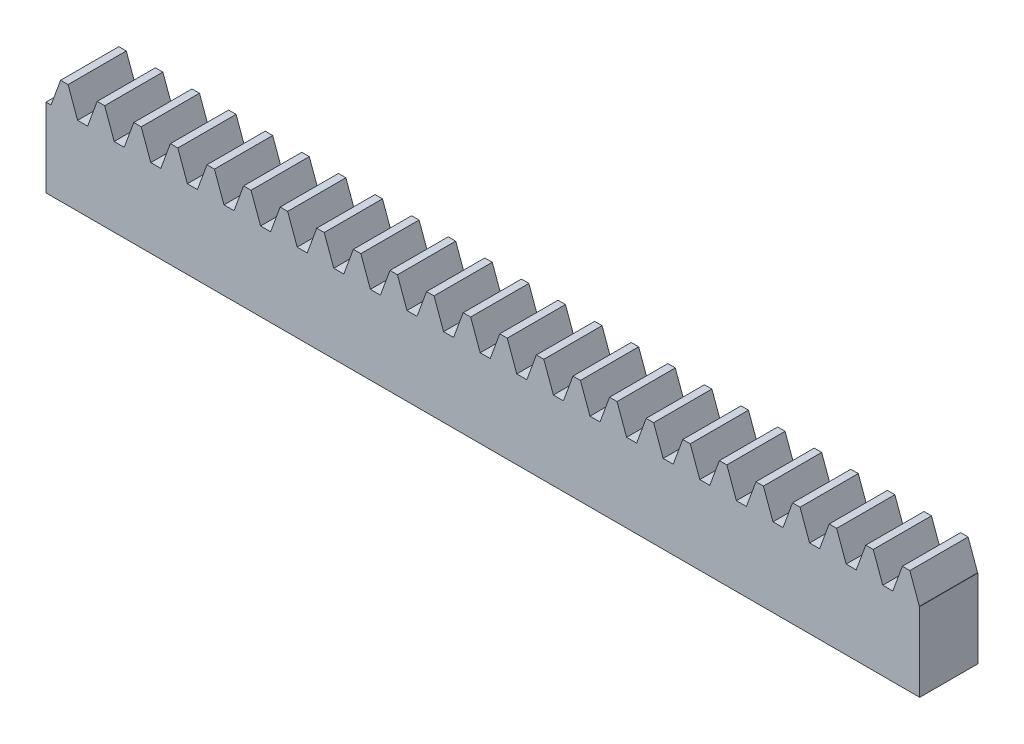
SolidWorks part; units mm, degrees
extrude "Blank" add sketch "BlankSke" against normal blind 5
sketch "BlankSke" plane through (0, 0, 0) normal (0, 0, 1) x (1, 0, 0)
  line L1 (0, 0) -> (150, 0)
  line L2 (0, 0) -> (0, 12)
  line L3 (0, 12) -> (150, 12)
  line L4 (150, 0) -> (150, 12)
  dimension "Length" = 150
  dimension "Blank_height" = 12
ref_plane "Plane1" through (0, 0, 0) normal (0, 0, 1) x (1, 0, 0)
ref_plane "Plane2" through (0, 0, 0) normal (0, 1, 0) x (1, 0, 0)
ref_plane "Plane3" through (0, 0, 0) normal (1, 0, 0) x (0, 0, -1)
sketch "HoldingSke" plane through (0, 0, 0) normal (0, 1, 0) x (1, 0, 0)
  line L0 (0, 0) -> (0.0696, 0.4951)
  line L1 (-15, 0) -> (100, 0) construction
  line L2 (0, 0) -> (-2.1039, 2.3779)
  line L3 (0, 0) -> (-11.863, 4.5341)
  line L4 (0, 0) -> (7.8269, 3.6497)
  line L5 (0, 0) -> (-23.7986, -8.8762)
  line L6 (0, 0) -> (-10.5278, -7.1032)
  line L9 (-71.009, 38.7566) -> (69.9449, 90.0596)
  line L10 (-76.2, 4.3779) -> (-66.2, 4.3779)
  line L11 (0, 0) -> (-5, 0)
  line L12 (-76.2, 101.6) -> (-76.133, 101.6)
  line L13 (24.9733, 27.94) -> (52.9518, 28.4284)
  line L14 (24.9733, 27.94) -> (24.9743, 27.94)
  line L15 (24.9733, 27.94) -> (100.4006, 29.5858)
  circle A0 centre (0, 0) radius 19.05
  circle A1 centre (0, 0) radius 5
  circle A2 centre (0, 0) radius 12.7
  dimension "MPH" = 10
  dimension "Diameter" = 38.1
  dimension "Num_teeth" = 25
  dimension "Pitch" = 0.5
  dimension "Show_teeth" = 998
  dimension "Thickness" = 12.7
  dimension "Ap" = 20
  dimension "Pitch_height" = 10
  dimension "Width" = 5
  dimension "Backlash" = 0.067
  dimension "Addendum_fac" = 1
  dimension "Dedendum_fac" = 1.25
  dimension "Clearance_fac" = 0.25
  dimension "Dedendum_add" = 0.001
  dimension "Length" = 150
  dimension "Module" = 2
sketch "TooCutSkeIll" plane through (0, 0, 0) normal (0, 0, 1) x (1, 0, 0)
  line L0 (-2.4806, 11.9474) -> (-0.9819, 7.8296)
  line L1 (-0.5111, 7.5) -> (0.5111, 7.5)
  line L2 (0.9819, 7.8296) -> (2.4806, 11.9474)
  line L3 (150, 12) -> (0, 12) construction
  line L4 (0, 0) -> (0, 64.897) construction
  line L5 (-13.208, 10) -> (12.954, 10) construction
  line L6 (0, 0) -> (150, 0) construction
  line L7 (1.7718, 10) -> (1.7718, 48.7463) construction
  line L8 (-1.7718, 10) -> (-1.7718, 48.7463) construction
  line L9 (2.5558, 12) -> (2.5558, 12.0254)
  line L10 (-2.5558, 12) -> (-2.5558, 12.0254)
  line L11 (-2.5558, 12.0254) -> (2.5558, 12.0254)
  arc A0 (0.5111, 7.5) -> (0.9819, 7.8296) centre (0.5111, 8.001) ccw
  arc A1 (-0.9819, 7.8296) -> (-0.5111, 7.5) centre (-0.5111, 8.001) ccw
  arc A2 (2.5558, 12) -> (2.4806, 11.9474) centre (2.5558, 11.92) ccw
  arc A3 (-2.4806, 11.9474) -> (-2.5558, 12) centre (-2.5558, 11.92) ccw
  dimension "Pitch_height" = 10
  dimension "Addendum_plus" = 2.0254
  dimension "Pressure_angle" = 20
  dimension "Gap_width" = 3.5436
  dimension "Dedendum" = 2.5
extrude "ToothCutIll" [suppressed] cut sketch "TooCutSkeIll" against normal through all
sketch "TooCutSkeSim" plane through (0, 0, 0) normal (0, 0, 1) x (1, 0, 0)
  line L0 (0.8619, 7.5) -> (-0.8619, 7.5)
  line L1 (2.509, 12.0254) -> (0.8619, 7.5)
  line L2 (0, 17.4625) -> (0, 53.467) construction
  line L3 (2.509, 12.0254) -> (-2.509, 12.0254)
  line L6 (-2.509, 12.0254) -> (-0.8619, 7.5)
  line L9 (-1.7718, 10) -> (1.7718, 10) construction
  line L10 (0, 0) -> (150, 0) construction
  line L11 (1.7718, 10) -> (1.7718, 53.467) construction
  line L12 (-1.7718, 10) -> (-1.7718, 53.467) construction
  dimension "Pitch_height" = 10
  dimension "Addendum_plus" = 2.0254
  dimension "Pressure_angle" = 20
  dimension "Gap_width" = 3.5436
  dimension "Dedendum" = 2.5
extrude "ToothCutSim" cut sketch "TooCutSkeSim" against normal through all
pattern_linear "TeethCuts" count 25 spacing 6.2832 along (1, 0, 0) of "ToothCutIll", "ToothCutSim"
ref_plane "Plane4" through (0, 0, -2.5) normal (0, 0, 1) x (1, 0, 0)
sketch "Sketch1" plane through (0, 0, -5) normal (0, 0, -1) x (-1, 0, 0)
  line L0 (-147.013, 12) -> (-147.013, 0)
  line L1 (-150, 0) -> (0, 0)
  line L2 (-150, 0) -> (-150, -6)
  line L3 (-150, -6) -> (0, -6)
  line L4 (0, 0) -> (0, -6)
  dimension "D1" = 12
  dimension "D2" = 6
extrude "Boss-Extrude1" add sketch "Sketch1" against normal blind 10 contours L4 L3 L2 L1
ref_plane "Plane5" through (0, 0, 0) normal (0, 0, 1) x (1, 0, 0)
mirror "Mirror1" about plane through (0, 0, 0) normal (0, 0, 1) of "TeethCuts", "Blank"
sketch "Sketch3" plane through (0, -6, 0) normal (0, -1, 0) x (-1, 0, 0)
  line L0 (-150, 0) -> (-100, 0)
  line L1 (-150, -5) -> (-150, 5) construction
  line L2 (-100, 0) -> (-50, 0)
  line L3 (-50, 0) -> (0, 0)
  line L4 (0, -5) -> (0, 5) construction
  dimension "D1" = 50
  dimension "D2" = 50
hole_wizard "Ø4.0mm Dowel Hole1" positions "Sketch4" profile "Sketch6" hole size "Ø4.0" standard "ANSI Metric"
sketch "Sketch4" plane through (0, -6, 0) normal (0, -1, 0) x (-1, 0, 0)
  point P0 (-50, 0)
  point P3 (-100, 0)
sketch "Sketch6" plane through (50, -6, 0) normal (1, 0, 0) x (0, 0, -1)
  line L0 (0, 0) -> (0, 4.2017)
  line L1 (0, 4.2017) -> (2, 3)
  line L2 (2, 3) -> (2, 0.025)
  line L3 (2, 0.025) -> (2.025, 0)
  line L5 (2.025, 0) -> (0, 0)
  line L6 (-2, 0.025) -> (-2.025, 0) construction
  line L10 (0, 4.2017) -> (-2, 3) construction
  line L11 (0, -6.35) -> (0, 107.95) construction
  dimension "Hole Dia." = 4
  dimension "Hole Depth" = 3
  dimension "Near C'Sink Dia." = 4.05
  dimension "Near C'Sink Angle" = 90
  dimension "Drill Angle" = 118
sketch "Sketch7" plane through (0, 0, -5) normal (0, 0, -1) x (-1, 0, 0)
  line L0 (-100, -6) -> (-100, -3)
  line L1 (-150, -6) -> (-100, -6) construction
  line L2 (-100, -6) -> (-50, -6) construction
  line L3 (-50, -6) -> (-50, -3)
  line L4 (-50, -6) -> (0, -6) construction
  line L5 (-100, -3) -> (-106, -3)
  line L6 (-75, -6) -> (-75, 0)
  line L7 (-106, -3) -> (-94, -3)
  line L8 (-106, -3) -> (-106, 3)
  line L9 (-106, 3) -> (-94, 3)
  line L10 (-94, -3) -> (-94, 3)
  line L11 (-44, 3) -> (-56, 3)
  line L12 (-56, -3) -> (-56, 3)
  line L13 (-44, -3) -> (-56, -3)
  line L14 (-44, -3) -> (-44, 3)
  dimension "D1" = 3
  dimension "D2" = 6
  dimension "D3" = 12
  dimension "D4" = 6
  dimension "D5" = 25
extrude "Cut-Extrude1" cut sketch "Sketch7" against normal blind 9.2 contours L7 L10 L9 L8 L5 | L13 L14 L11 L12
fillet "Fillet2" radius 5 2 edges at (94, 3, -0.4) (106, 3, -0.4)
fillet "Fillet3" radius 5 2 edges at (56, 3, -0.4) (44, 3, -0.4)
equation "' \"Module@HoldingSke\" = 6.35"
equation "' \"Num_teeth@HoldingSke\" = 12"
equation "' \"Ap@HoldingSke\" =  20"
equation "' \"Ap@HoldingSke\" = 20"
equation "' \"Width@HoldingSke\" = 0.25 * 25.4"
equation "' \"Show_teeth@HoldingSke\" = 500"
equation "' \"Backlash@HoldingSke\" = 0.009 * 25.4"
equation "' \"Addendum_fac@HoldingSke\" = 1.0"
equation "' \"Dedendum_fac@HoldingSke\" = 1.25"
equation "' \"Dedendum_add@HoldingSke\" = 0.00005 * 25.4"
equation "' \"Clearance_fac@HoldingSke\" = 0.25"
equation "' \"Pitch_height@HoldingSke\" = 1 * 25.4"
equation "' \"Length@HoldingSke\" = 4.71 * 25.4"
equation "\"Pitch@HoldingSke\" = 1 / \"Module@HoldingSke\""
equation "\"MPH@HoldingSke\" = \"Dedendum_fac@HoldingSke\" / \"Pitch@HoldingSke\" + 2 * \"Dedendum_add@HoldingSke\" + 0.002 * 25.4"
equation "\"MPH@HoldingSke\" = ((sgn( \"MPH@HoldingSke\" - \"Pitch_height@HoldingSke\")+1)*( \"MPH@HoldingSke\" - \"Pitch_height@HoldingSke\"))/2 + \"Pitch_height@HoldingSke\""
equation "\"Blank_height@BlankSke\" = \"Pitch_height@HoldingSke\" + \"Addendum_fac@HoldingSke\"  / \"Pitch@HoldingSke\" "
equation "\"Length@BlankSke\" =  \"Length@HoldingSke\""
equation "\"Face_width@Blank\" = \"Width@HoldingSke\""
equation "\"Pressure_angle@TooCutSkeIll\" = \"Ap@HoldingSke\""
equation "\"Addendum_plus@TooCutSkeIll\" =  \"Addendum_fac@HoldingSke\"  / \"Pitch@HoldingSke\" + 0.001 *25.4"
equation "\"Dedendum@TooCutSkeIll\" = \"Dedendum_fac@HoldingSke\"  / \"Pitch@HoldingSke\""
equation "\"Pitch_height@TooCutSkeIll\" =  \"MPH@HoldingSke\""
equation "\"Gap_width@TooCutSkeIll\" = 3.14159265 / 2 / \"Pitch@HoldingSke\" + 6 * \"Backlash@HoldingSke\""
equation "\"Pressure_angle@TooCutSkeSim\" = \"Ap@HoldingSke\""
equation "\"Addendum_plus@TooCutSkeSim\" =  \"Addendum_fac@HoldingSke\"  / \"Pitch@HoldingSke\" + 0.001 * 25.4"
equation "\"Dedendum@TooCutSkeSim\" = \"Dedendum_fac@HoldingSke\"  / \"Pitch@HoldingSke\""
equation "\"Pitch_height@TooCutSkeSim\" =  \"MPH@HoldingSke\""
equation "\"Gap_width@TooCutSkeSim\" = 3.14159265 / 2 / \"Pitch@HoldingSke\" + 6 * \"Backlash@HoldingSke\""
equation "\"Root_fillet@TooCutSkeIll\" = \"Clearance_fac@HoldingSke\" / \"Pitch@HoldingSke\" + \"Dedendum_add@HoldingSke\""
equation "\"Break_rad@TooCutSkeIll\" = 0.02 / \"Pitch@HoldingSke\" * 2"
equation "\"Linear_pitch@TeethCuts\" = 3.14159265 / \"Pitch@HoldingSke\""
equation "\"Num_teeth@HoldingSke\" = int( ( \"Length@HoldingSke\" + 0 ) / (3.14159265 / \"Pitch@HoldingSke\")) + 0.9999  + 1"
equation " \"Num_teeth@TeethCuts\" = int( \"Show_teeth@HoldingSke\" ) + 1"
equation " \"Num_teeth@TeethCuts\" = ((sgn( \"Num_teeth@TeethCuts\" - \"Num_teeth@HoldingSke\" )-1)*( \"Num_teeth@TeethCuts\" - \"Num_teeth@HoldingSke\" ))/-2+ \"Num_teeth@HoldingSke\""
equation " \"Num_teeth@TeethCuts\" = ((sgn( \"Num_teeth@TeethCuts\" - 2.0)+1)*( \"Num_teeth@TeethCuts\" - 2.0))/2 +2.0"
